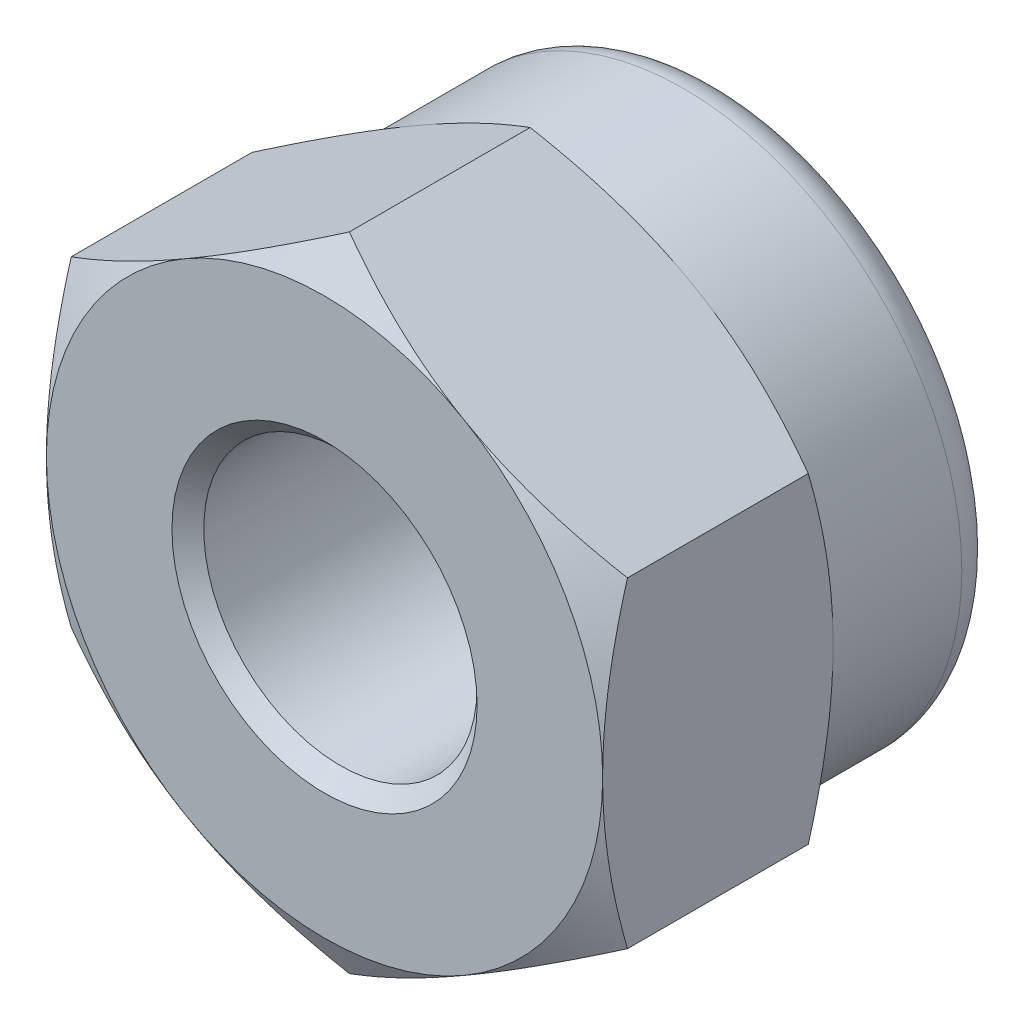
SolidWorks part; units mm, degrees
ref_plane "前视基准面" through (0, 0, 0) normal (0, 0, 1) x (1, 0, 0)
ref_plane "上视基准面" through (0, 0, 0) normal (0, 1, 0) x (1, 0, 0)
ref_plane "右视基准面" through (0, 0, 0) normal (1, 0, 0) x (0, 0, -1)
sketch "草图1" plane through (0, 0, 0) normal (0, 0, 1) x (1, 0, 0)
  line L1 (0, 4.0415) -> (-3.5, 2.0207)
  line L2 (-3.5, 2.0207) -> (-3.5, -2.0207)
  line L3 (-3.5, -2.0207) -> (0, -4.0415)
  line L4 (0, -4.0415) -> (3.5, -2.0207)
  line L5 (3.5, -2.0207) -> (3.5, 2.0207)
  line L6 (3.5, 2.0207) -> (0, 4.0415)
  circle A0 centre (0, 0) radius 3.5 construction
  circle A1 centre (0, 0) radius 1.72
  dimension "D1" = 3.44
  dimension "D2" = 7
extrude "凸台-拉伸1" add sketch "草图1" against normal blind 2.9
cosmetic thread "装饰螺纹线1" parameters "D1"=2.9, "D2"=4
sketch "草图2" plane through (0, 0, 0) normal (1, 0, 0) x (0, 0, -1)
  line L0 (0, 3.5) -> (0.3126, 4.0415)
  line L1 (0, 2.0207) -> (0, 4.0415) construction
  line L2 (2.9, 4.0415) -> (0, 4.0415) construction
  line L3 (0.3126, 4.0415) -> (0, 4.0415)
  line L4 (0, 4.0415) -> (0, 3.5)
  line L5 (0, 0) -> (2.9, 0) construction
  line L6 (2.9, -2.0207) -> (2.9, 2.0207) construction
  line L7 (2.9, 3.5) -> (2.5874, 4.0415)
  line L8 (2.9, 2.0207) -> (2.9, 4.0415) construction
  line L9 (2.5874, 4.0415) -> (2.9, 4.0415)
  line L10 (2.9, 4.0415) -> (2.9, 3.5)
  dimension "D1" = 7
  dimension "D2" = 30
revolve "切除-旋转1" cut sketch "草图2" angle 360 about L5
chamfer "倒角1" [suppressed] distance 0.2 angle 45
sketch "草图3" [suppressed] plane through (0, 0, 0) normal (0, 0, 1) x (1, 0, 0)
  circle A0 centre (0, 0) radius 2.4
  circle A1 centre (0, 0) radius 3.5
  dimension "D1" = 4.8
extrude "凸台-拉伸2" [suppressed] add sketch "草图3" along normal blind 2.1
fillet "圆角1" [suppressed] radius 0.2
sketch "草图4" [suppressed] plane through (0, 0, 0) normal (0, 0, 1) x (1, 0, 0)
  line L0 (-1.72, 0) -> (-1.9596, 0)
  line L1 (-0.86, 1.4896) -> (-0.9798, 1.6971)
  arc A0 (-1.9596, 0) -> (-2.3515, 0.48) centre (-1.9596, 0.4) cw
  arc A1 (-1.5914, 1.7965) -> (-0.9798, 1.6971) centre (-1.3262, 1.4971) cw
  circle A3 centre (0, 0) radius 2.4 construction
  arc A4 (-1.5914, 1.7965) -> (-2.3515, 0.48) centre (0, 0) ccw
  arc A5 (-0.86, 1.4896) -> (-1.72, 0) centre (0, 0) ccw
  point P4 (-2.4, 0)
  dimension "D1" = 3.44
  dimension "D3" = 0.4
  dimension "D2" = 60
extrude "凸台-拉伸3" [suppressed] add sketch "草图4" along normal blind 1.05
pattern_circular "阵列(圆周)1" [suppressed] count 3 over 360
sketch "草图5" plane through (0, 0, -2.9) normal (0, 0, -1) x (-1, 0, 0)
  circle A0 centre (0, 0) radius 3.5
  circle A2 centre (0, 0) radius 2.2
  dimension "D1" = 4.4
extrude "凸台-拉伸4" add sketch "草图5" along normal blind 2.1
fillet "圆角2" radius 0.48 1 edges at (-3.5, 0, -5)
sketch "草图6" plane through (0, 0, -5) normal (0, 0, -1) x (-1, 0, 0)
  circle A0 centre (0, 0) radius 2.5
  dimension "D1" = 5
extrude "切除-拉伸1" cut sketch "草图6" against normal blind 0.525
chamfer "倒角2" distance 0.2 angle 45 2 edges at (1.72, 0, 0) (1.72, 0, -2.9)
equation "\"S\"=7"
equation "\"M\"=4"
equation "\"H\"=5"
equation "\"m_\"=2.9"
equation "\"D1@草图1\"  = \"M\" * .86"
equation "\"D2@草图1\" = \"S\""
equation "\"D1@凸台-拉伸1\"=\"m_\""
equation "\"D1@草图2\"=\"S\""
equation "\"D1@倒角1\"=\"M\"*.05"
equation "\"D1@草图3\"=\"M\"*1.2"
equation "\"D1@凸台-拉伸2\" = \"H\" - \"m_\""
equation "\"D1@圆角1\"=\"M\"*.05"
equation "\"D1@草图4\"=\"M\" * .86"
equation "\"D2@草图4\"  = \"AN\""
equation "\"D1@阵列(圆周)1\" = 180 / \"AN\""
equation "\"D1@凸台-拉伸3\"= \"H\" *.5- \"m_\"*.5"
equation "\"D2@装饰螺纹线1\"=\"M\""
equation "\"D1@草图5\"=\"M\"*1.1"
equation "\"D1@凸台-拉伸4\"= \"H\" - \"m_\""
equation "\"D1@圆角2\"=\"M\"*.12"
equation "\"D1@草图6\"=\"M\"*1.25"
equation "\"D1@切除-拉伸1\"= \"H\"*.25 - \"m_\"*.25"
equation "\"AN\"=60"
equation "\"D1@装饰螺纹线1\" = \"m_\""
equation "\"D1@倒角2\"=\"M\"*0.05"
equation "\"D3@草图4\"=\"M\"*0.1"
